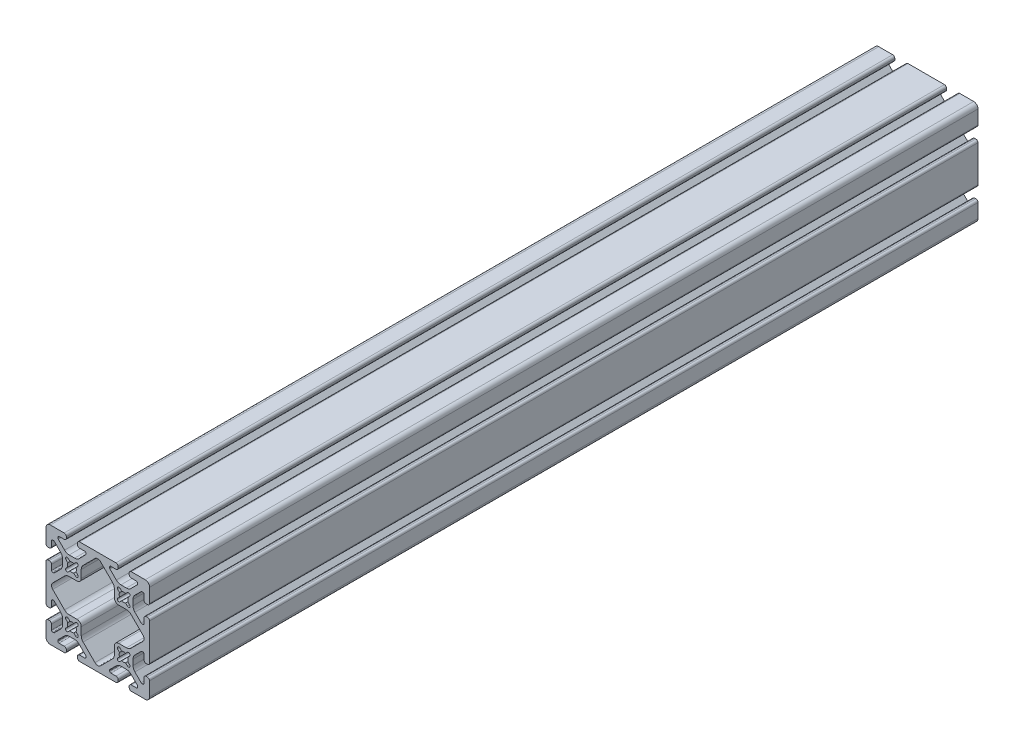
SolidWorks part; units mm, degrees
material "6063-T6"
ref_plane "Front Plane" through (0, 0, 0) normal (0, 0, 1) x (1, 0, 0)
ref_plane "Top Plane" through (0, 0, 0) normal (0, 1, 0) x (1, 0, 0)
ref_plane "Right Plane" through (0, 0, 0) normal (1, 0, 0) x (0, 0, -1)
ref_plane "Plane1" through (0, 0, -711.2) normal (0, 0, -1) x (-1, 0, 0)
sketch "Sketch1" plane through (0, 0, -711.2) normal (0, 0, -1) x (-1, 0, 0)
  line L0 (24.4372, 10.7892) -> (33.1609, 2.0655)
  line L1 (33.1609, -2.0655) -> (24.4372, -10.7892)
  line L2 (21.0785, -12.1803) -> (15.3553, -12.1803)
  line L3 (12.1803, -15.3553) -> (12.1803, -21.0785)
  line L4 (10.7892, -24.4372) -> (2.0655, -33.1609)
  line L5 (-2.0655, -33.1609) -> (-10.7892, -24.4372)
  line L6 (-12.1803, -21.0785) -> (-12.1803, -15.3553)
  line L7 (-15.3553, -12.1803) -> (-21.0785, -12.1803)
  line L8 (-24.4372, -10.7892) -> (-33.1609, -2.0655)
  line L9 (-33.1609, 2.0655) -> (-24.4372, 10.7892)
  line L10 (-21.0785, 12.1803) -> (-15.3553, 12.1803)
  line L11 (-12.1803, 15.3553) -> (-12.1803, 21.0785)
  line L12 (-10.7892, 24.4372) -> (-2.0655, 33.1609)
  line L13 (2.0655, 33.1609) -> (10.7892, 24.4372)
  line L14 (12.1803, 21.0785) -> (12.1803, 15.3553)
  line L15 (15.3553, 12.1803) -> (21.0785, 12.1803)
  line L16 (22.0679, 17.6486) -> (23.3933, 16.3231)
  line L17 (21.7769, 14.7067) -> (20.4514, 16.0321)
  line L18 (17.6486, 16.0321) -> (16.3231, 14.7067)
  line L19 (14.7067, 16.3231) -> (16.0321, 17.6486)
  line L20 (16.0321, 20.4514) -> (14.7067, 21.7769)
  line L21 (16.3231, 23.3933) -> (17.6486, 22.0679)
  line L22 (20.4514, 22.0679) -> (21.7769, 23.3933)
  line L23 (23.3933, 21.7769) -> (22.0679, 20.4514)
  line L24 (20.4514, -16.0321) -> (21.7769, -14.7067)
  line L25 (23.3933, -16.3231) -> (22.0679, -17.6486)
  line L26 (22.0679, -20.4514) -> (23.3933, -21.7769)
  line L27 (21.7769, -23.3933) -> (20.4514, -22.0679)
  line L28 (17.6486, -22.0679) -> (16.3231, -23.3933)
  line L29 (14.7067, -21.7769) -> (16.0321, -20.4514)
  line L30 (16.0321, -17.6486) -> (14.7067, -16.3231)
  line L31 (16.3231, -14.7067) -> (17.6486, -16.0321)
  line L32 (-16.0321, 17.6486) -> (-14.7067, 16.3231)
  line L33 (-16.3231, 14.7067) -> (-17.6486, 16.0321)
  line L34 (-20.4514, 16.0321) -> (-21.7769, 14.7067)
  line L35 (-23.3933, 16.3231) -> (-22.0679, 17.6486)
  line L36 (-22.0679, 20.4514) -> (-23.3933, 21.7769)
  line L37 (-21.7769, 23.3933) -> (-20.4514, 22.0679)
  line L38 (-17.6486, 22.0679) -> (-16.3231, 23.3933)
  line L39 (-14.7067, 21.7769) -> (-16.0321, 20.4514)
  line L40 (-17.6486, -16.0321) -> (-16.3231, -14.7067)
  line L41 (-14.7067, -16.3231) -> (-16.0321, -17.6486)
  line L42 (-16.0321, -20.4514) -> (-14.7067, -21.7769)
  line L43 (-16.3231, -23.3933) -> (-17.6486, -22.0679)
  line L44 (-20.4514, -22.0679) -> (-21.7769, -23.3933)
  line L45 (-23.3933, -21.7769) -> (-22.0679, -20.4514)
  line L46 (-22.0679, -17.6486) -> (-23.3933, -16.3231)
  line L47 (-21.7769, -14.7067) -> (-20.4514, -16.0321)
  line L48 (36.5252, 14.986) -> (35.6108, 14.986)
  line L49 (34.036, 13.4112) -> (34.036, 9.652)
  line L50 (33.147, 8.763) -> (32.5789, 8.763)
  line L51 (31.9503, 9.0234) -> (27.3108, 13.6628)
  line L52 (25.9197, 17.0215) -> (25.9197, 21.0785)
  line L53 (27.3108, 24.4372) -> (31.9503, 29.0766)
  line L54 (32.5789, 29.337) -> (33.147, 29.337)
  line L55 (34.036, 28.448) -> (34.036, 24.6888)
  line L56 (35.6108, 23.114) -> (36.5252, 23.114)
  line L57 (38.1, 24.6888) -> (38.1, 34.925)
  line L58 (34.925, 38.1) -> (24.6888, 38.1)
  line L59 (23.114, 36.5252) -> (23.114, 35.6108)
  line L60 (24.6888, 34.036) -> (28.448, 34.036)
  line L61 (29.337, 33.147) -> (29.337, 32.5789)
  line L62 (29.0766, 31.9503) -> (24.4372, 27.3108)
  line L63 (21.0785, 25.9197) -> (17.0215, 25.9197)
  line L64 (13.6628, 27.3108) -> (9.0234, 31.9503)
  line L65 (8.763, 32.5789) -> (8.763, 33.147)
  line L66 (9.652, 34.036) -> (13.4112, 34.036)
  line L67 (14.986, 35.6108) -> (14.986, 36.5252)
  line L68 (13.4112, 38.1) -> (-13.4112, 38.1)
  line L69 (-14.986, 36.5252) -> (-14.986, 35.6108)
  line L70 (-13.4112, 34.036) -> (-9.652, 34.036)
  line L71 (-8.763, 33.147) -> (-8.763, 32.5789)
  line L72 (-9.0234, 31.9503) -> (-13.6628, 27.3108)
  line L73 (-17.0215, 25.9197) -> (-21.0785, 25.9197)
  line L74 (-24.4372, 27.3108) -> (-29.0766, 31.9503)
  line L75 (-29.337, 32.5789) -> (-29.337, 33.147)
  line L76 (-28.448, 34.036) -> (-24.6888, 34.036)
  line L77 (-23.114, 35.6108) -> (-23.114, 36.5252)
  line L78 (-24.6888, 38.1) -> (-34.925, 38.1)
  line L79 (-38.1, 34.925) -> (-38.1, 24.6888)
  line L80 (-36.5252, 23.114) -> (-35.6108, 23.114)
  line L81 (-34.036, 24.6888) -> (-34.036, 28.448)
  line L82 (-33.147, 29.337) -> (-32.5789, 29.337)
  line L83 (-31.9503, 29.0766) -> (-27.3108, 24.4372)
  line L84 (-25.9197, 21.0785) -> (-25.9197, 17.0215)
  line L85 (-27.3108, 13.6628) -> (-31.9503, 9.0234)
  line L86 (-32.5789, 8.763) -> (-33.147, 8.763)
  line L87 (-34.036, 9.652) -> (-34.036, 13.4112)
  line L88 (-35.6108, 14.986) -> (-36.5252, 14.986)
  line L89 (-38.1, 13.4112) -> (-38.1, -13.4112)
  line L90 (-36.5252, -14.986) -> (-35.6108, -14.986)
  line L91 (-34.036, -13.4112) -> (-34.036, -9.652)
  line L92 (-33.147, -8.763) -> (-32.5789, -8.763)
  line L93 (-31.9503, -9.0234) -> (-27.3108, -13.6628)
  line L94 (-25.9197, -17.0215) -> (-25.9197, -21.0785)
  line L95 (-27.3108, -24.4372) -> (-31.9503, -29.0766)
  line L96 (-32.5789, -29.337) -> (-33.147, -29.337)
  line L97 (-34.036, -28.448) -> (-34.036, -24.6888)
  line L98 (-35.6108, -23.114) -> (-36.5252, -23.114)
  line L99 (-38.1, -24.6888) -> (-38.1, -34.925)
  line L100 (-34.925, -38.1) -> (-24.6888, -38.1)
  line L101 (-23.114, -36.5252) -> (-23.114, -35.6108)
  line L102 (-24.6888, -34.036) -> (-28.448, -34.036)
  line L103 (-29.337, -33.147) -> (-29.337, -32.5789)
  line L104 (-29.0766, -31.9503) -> (-24.4372, -27.3108)
  line L105 (-21.0785, -25.9197) -> (-17.0215, -25.9197)
  line L106 (-13.6628, -27.3108) -> (-9.0234, -31.9503)
  line L107 (-8.763, -32.5789) -> (-8.763, -33.147)
  line L108 (-9.652, -34.036) -> (-13.4112, -34.036)
  line L109 (-14.986, -35.6108) -> (-14.986, -36.5252)
  line L110 (-13.4112, -38.1) -> (13.4112, -38.1)
  line L111 (14.986, -36.5252) -> (14.986, -35.6108)
  line L112 (13.4112, -34.036) -> (9.652, -34.036)
  line L113 (8.763, -33.147) -> (8.763, -32.5789)
  line L114 (9.0234, -31.9503) -> (13.6628, -27.3108)
  line L115 (17.0215, -25.9197) -> (21.0785, -25.9197)
  line L116 (24.4372, -27.3108) -> (29.0766, -31.9503)
  line L117 (29.337, -32.5789) -> (29.337, -33.147)
  line L118 (28.448, -34.036) -> (24.6888, -34.036)
  line L119 (23.114, -35.6108) -> (23.114, -36.5252)
  line L120 (24.6888, -38.1) -> (34.925, -38.1)
  line L121 (38.1, -34.925) -> (38.1, -24.6888)
  line L122 (36.5252, -23.114) -> (35.6108, -23.114)
  line L123 (34.036, -24.6888) -> (34.036, -28.448)
  line L124 (33.147, -29.337) -> (32.5789, -29.337)
  line L125 (31.9503, -29.0766) -> (27.3108, -24.4372)
  line L126 (25.9197, -21.0785) -> (25.9197, -17.0215)
  line L127 (27.3108, -13.6628) -> (31.9503, -9.0234)
  line L128 (32.5789, -8.763) -> (33.147, -8.763)
  line L129 (34.036, -9.652) -> (34.036, -13.4112)
  line L130 (35.6108, -14.986) -> (36.5252, -14.986)
  line L131 (38.1, -13.4112) -> (38.1, 13.4112)
  arc A0 (33.1609, 2.0655) -> (33.1609, -2.0655) centre (31.0954, 0) cw
  arc A1 (24.4372, -10.7892) -> (21.0785, -12.1803) centre (21.0785, -7.4305) cw
  arc A2 (15.3553, -12.1803) -> (12.1803, -15.3553) centre (15.3553, -15.3553) ccw
  arc A3 (12.1803, -21.0785) -> (10.7892, -24.4372) centre (7.4305, -21.0785) cw
  arc A4 (2.0655, -33.1609) -> (-2.0655, -33.1609) centre (0, -31.0954) cw
  arc A5 (-10.7892, -24.4372) -> (-12.1803, -21.0785) centre (-7.4305, -21.0785) cw
  arc A6 (-12.1803, -15.3553) -> (-15.3553, -12.1803) centre (-15.3553, -15.3553) ccw
  arc A7 (-21.0785, -12.1803) -> (-24.4372, -10.7892) centre (-21.0785, -7.4305) cw
  arc A8 (-33.1609, -2.0655) -> (-33.1609, 2.0655) centre (-31.0954, 0) cw
  arc A9 (-24.4372, 10.7892) -> (-21.0785, 12.1803) centre (-21.0785, 7.4305) cw
  arc A10 (-15.3553, 12.1803) -> (-12.1803, 15.3553) centre (-15.3553, 15.3553) ccw
  arc A11 (-12.1803, 21.0785) -> (-10.7892, 24.4372) centre (-7.4305, 21.0785) cw
  arc A12 (-2.0655, 33.1609) -> (2.0655, 33.1609) centre (0, 31.0954) cw
  arc A13 (10.7892, 24.4372) -> (12.1803, 21.0785) centre (7.4305, 21.0785) cw
  arc A14 (12.1803, 15.3553) -> (15.3553, 12.1803) centre (15.3553, 15.3553) ccw
  arc A15 (21.0785, 12.1803) -> (24.4372, 10.7892) centre (21.0785, 7.4305) cw
  arc A16 (23.3933, 16.3231) -> (21.7769, 14.7067) centre (22.5851, 15.5149) cw
  arc A17 (20.4514, 16.0321) -> (17.6486, 16.0321) centre (19.05, 19.05) cw
  arc A18 (16.3231, 14.7067) -> (14.7067, 16.3231) centre (15.5149, 15.5149) cw
  arc A19 (16.0321, 17.6486) -> (16.0321, 20.4514) centre (19.05, 19.05) cw
  arc A20 (14.7067, 21.7769) -> (16.3231, 23.3933) centre (15.5149, 22.5851) cw
  arc A21 (17.6486, 22.0679) -> (20.4514, 22.0679) centre (19.05, 19.05) cw
  arc A22 (21.7769, 23.3933) -> (23.3933, 21.7769) centre (22.5851, 22.5851) cw
  arc A23 (22.0679, 20.4514) -> (22.0679, 17.6486) centre (19.05, 19.05) cw
  arc A24 (21.7769, -14.7067) -> (23.3933, -16.3231) centre (22.5851, -15.5149) cw
  arc A25 (22.0679, -17.6486) -> (22.0679, -20.4514) centre (19.05, -19.05) cw
  arc A26 (23.3933, -21.7769) -> (21.7769, -23.3933) centre (22.5851, -22.5851) cw
  arc A27 (20.4514, -22.0679) -> (17.6486, -22.0679) centre (19.05, -19.05) cw
  arc A28 (16.3231, -23.3933) -> (14.7067, -21.7769) centre (15.5149, -22.5851) cw
  arc A29 (16.0321, -20.4514) -> (16.0321, -17.6486) centre (19.05, -19.05) cw
  arc A30 (14.7067, -16.3231) -> (16.3231, -14.7067) centre (15.5149, -15.5149) cw
  arc A31 (17.6486, -16.0321) -> (20.4514, -16.0321) centre (19.05, -19.05) cw
  arc A32 (-14.7067, 16.3231) -> (-16.3231, 14.7067) centre (-15.5149, 15.5149) cw
  arc A33 (-17.6486, 16.0321) -> (-20.4514, 16.0321) centre (-19.05, 19.05) cw
  arc A34 (-21.7769, 14.7067) -> (-23.3933, 16.3231) centre (-22.5851, 15.5149) cw
  arc A35 (-22.0679, 17.6486) -> (-22.0679, 20.4514) centre (-19.05, 19.05) cw
  arc A36 (-23.3933, 21.7769) -> (-21.7769, 23.3933) centre (-22.5851, 22.5851) cw
  arc A37 (-20.4514, 22.0679) -> (-17.6486, 22.0679) centre (-19.05, 19.05) cw
  arc A38 (-16.3231, 23.3933) -> (-14.7067, 21.7769) centre (-15.5149, 22.5851) cw
  arc A39 (-16.0321, 20.4514) -> (-16.0321, 17.6486) centre (-19.05, 19.05) cw
  arc A40 (-16.3231, -14.7067) -> (-14.7067, -16.3231) centre (-15.5149, -15.5149) cw
  arc A41 (-16.0321, -17.6486) -> (-16.0321, -20.4514) centre (-19.05, -19.05) cw
  arc A42 (-14.7067, -21.7769) -> (-16.3231, -23.3933) centre (-15.5149, -22.5851) cw
  arc A43 (-17.6486, -22.0679) -> (-20.4514, -22.0679) centre (-19.05, -19.05) cw
  arc A44 (-21.7769, -23.3933) -> (-23.3933, -21.7769) centre (-22.5851, -22.5851) cw
  arc A45 (-22.0679, -20.4514) -> (-22.0679, -17.6486) centre (-19.05, -19.05) cw
  arc A46 (-23.3933, -16.3231) -> (-21.7769, -14.7067) centre (-22.5851, -15.5149) cw
  arc A47 (-20.4514, -16.0321) -> (-17.6486, -16.0321) centre (-19.05, -19.05) cw
  arc A48 (38.1, 13.4112) -> (36.5252, 14.986) centre (36.5252, 13.4112) ccw
  arc A49 (35.6108, 14.986) -> (34.036, 13.4112) centre (35.6108, 13.4112) ccw
  arc A50 (34.036, 9.652) -> (33.147, 8.763) centre (33.147, 9.652) cw
  arc A51 (32.5789, 8.763) -> (31.9503, 9.0234) centre (32.5789, 9.652) cw
  arc A52 (27.3108, 13.6628) -> (25.9197, 17.0215) centre (30.6695, 17.0215) cw
  arc A53 (25.9197, 21.0785) -> (27.3108, 24.4372) centre (30.6695, 21.0785) cw
  arc A54 (31.9503, 29.0766) -> (32.5789, 29.337) centre (32.5789, 28.448) cw
  arc A55 (33.147, 29.337) -> (34.036, 28.448) centre (33.147, 28.448) cw
  arc A56 (34.036, 24.6888) -> (35.6108, 23.114) centre (35.6108, 24.6888) ccw
  arc A57 (36.5252, 23.114) -> (38.1, 24.6888) centre (36.5252, 24.6888) ccw
  arc A58 (38.1, 34.925) -> (34.925, 38.1) centre (34.925, 34.925) ccw
  arc A59 (24.6888, 38.1) -> (23.114, 36.5252) centre (24.6888, 36.5252) ccw
  arc A60 (23.114, 35.6108) -> (24.6888, 34.036) centre (24.6888, 35.6108) ccw
  arc A61 (28.448, 34.036) -> (29.337, 33.147) centre (28.448, 33.147) cw
  arc A62 (29.337, 32.5789) -> (29.0766, 31.9503) centre (28.448, 32.5789) cw
  arc A63 (24.4372, 27.3108) -> (21.0785, 25.9197) centre (21.0785, 30.6695) cw
  arc A64 (17.0215, 25.9197) -> (13.6628, 27.3108) centre (17.0215, 30.6695) cw
  arc A65 (9.0234, 31.9503) -> (8.763, 32.5789) centre (9.652, 32.5789) cw
  arc A66 (8.763, 33.147) -> (9.652, 34.036) centre (9.652, 33.147) cw
  arc A67 (13.4112, 34.036) -> (14.986, 35.6108) centre (13.4112, 35.6108) ccw
  arc A68 (14.986, 36.5252) -> (13.4112, 38.1) centre (13.4112, 36.5252) ccw
  arc A69 (-13.4112, 38.1) -> (-14.986, 36.5252) centre (-13.4112, 36.5252) ccw
  arc A70 (-14.986, 35.6108) -> (-13.4112, 34.036) centre (-13.4112, 35.6108) ccw
  arc A71 (-9.652, 34.036) -> (-8.763, 33.147) centre (-9.652, 33.147) cw
  arc A72 (-8.763, 32.5789) -> (-9.0234, 31.9503) centre (-9.652, 32.5789) cw
  arc A73 (-13.6628, 27.3108) -> (-17.0215, 25.9197) centre (-17.0215, 30.6695) cw
  arc A74 (-21.0785, 25.9197) -> (-24.4372, 27.3108) centre (-21.0785, 30.6695) cw
  arc A75 (-29.0766, 31.9503) -> (-29.337, 32.5789) centre (-28.448, 32.5789) cw
  arc A76 (-29.337, 33.147) -> (-28.448, 34.036) centre (-28.448, 33.147) cw
  arc A77 (-24.6888, 34.036) -> (-23.114, 35.6108) centre (-24.6888, 35.6108) ccw
  arc A78 (-23.114, 36.5252) -> (-24.6888, 38.1) centre (-24.6888, 36.5252) ccw
  arc A79 (-34.925, 38.1) -> (-38.1, 34.925) centre (-34.925, 34.925) ccw
  arc A80 (-38.1, 24.6888) -> (-36.5252, 23.114) centre (-36.5252, 24.6888) ccw
  arc A81 (-35.6108, 23.114) -> (-34.036, 24.6888) centre (-35.6108, 24.6888) ccw
  arc A82 (-34.036, 28.448) -> (-33.147, 29.337) centre (-33.147, 28.448) cw
  arc A83 (-32.5789, 29.337) -> (-31.9503, 29.0766) centre (-32.5789, 28.448) cw
  arc A84 (-27.3108, 24.4372) -> (-25.9197, 21.0785) centre (-30.6695, 21.0785) cw
  arc A85 (-25.9197, 17.0215) -> (-27.3108, 13.6628) centre (-30.6695, 17.0215) cw
  arc A86 (-31.9503, 9.0234) -> (-32.5789, 8.763) centre (-32.5789, 9.652) cw
  arc A87 (-33.147, 8.763) -> (-34.036, 9.652) centre (-33.147, 9.652) cw
  arc A88 (-34.036, 13.4112) -> (-35.6108, 14.986) centre (-35.6108, 13.4112) ccw
  arc A89 (-36.5252, 14.986) -> (-38.1, 13.4112) centre (-36.5252, 13.4112) ccw
  arc A90 (-38.1, -13.4112) -> (-36.5252, -14.986) centre (-36.5252, -13.4112) ccw
  arc A91 (-35.6108, -14.986) -> (-34.036, -13.4112) centre (-35.6108, -13.4112) ccw
  arc A92 (-34.036, -9.652) -> (-33.147, -8.763) centre (-33.147, -9.652) cw
  arc A93 (-32.5789, -8.763) -> (-31.9503, -9.0234) centre (-32.5789, -9.652) cw
  arc A94 (-27.3108, -13.6628) -> (-25.9197, -17.0215) centre (-30.6695, -17.0215) cw
  arc A95 (-25.9197, -21.0785) -> (-27.3108, -24.4372) centre (-30.6695, -21.0785) cw
  arc A96 (-31.9503, -29.0766) -> (-32.5789, -29.337) centre (-32.5789, -28.448) cw
  arc A97 (-33.147, -29.337) -> (-34.036, -28.448) centre (-33.147, -28.448) cw
  arc A98 (-34.036, -24.6888) -> (-35.6108, -23.114) centre (-35.6108, -24.6888) ccw
  arc A99 (-36.5252, -23.114) -> (-38.1, -24.6888) centre (-36.5252, -24.6888) ccw
  arc A100 (-38.1, -34.925) -> (-34.925, -38.1) centre (-34.925, -34.925) ccw
  arc A101 (-24.6888, -38.1) -> (-23.114, -36.5252) centre (-24.6888, -36.5252) ccw
  arc A102 (-23.114, -35.6108) -> (-24.6888, -34.036) centre (-24.6888, -35.6108) ccw
  arc A103 (-28.448, -34.036) -> (-29.337, -33.147) centre (-28.448, -33.147) cw
  arc A104 (-29.337, -32.5789) -> (-29.0766, -31.9503) centre (-28.448, -32.5789) cw
  arc A105 (-24.4372, -27.3108) -> (-21.0785, -25.9197) centre (-21.0785, -30.6695) cw
  arc A106 (-17.0215, -25.9197) -> (-13.6628, -27.3108) centre (-17.0215, -30.6695) cw
  arc A107 (-9.0234, -31.9503) -> (-8.763, -32.5789) centre (-9.652, -32.5789) cw
  arc A108 (-8.763, -33.147) -> (-9.652, -34.036) centre (-9.652, -33.147) cw
  arc A109 (-13.4112, -34.036) -> (-14.986, -35.6108) centre (-13.4112, -35.6108) ccw
  arc A110 (-14.986, -36.5252) -> (-13.4112, -38.1) centre (-13.4112, -36.5252) ccw
  arc A111 (13.4112, -38.1) -> (14.986, -36.5252) centre (13.4112, -36.5252) ccw
  arc A112 (14.986, -35.6108) -> (13.4112, -34.036) centre (13.4112, -35.6108) ccw
  arc A113 (9.652, -34.036) -> (8.763, -33.147) centre (9.652, -33.147) cw
  arc A114 (8.763, -32.5789) -> (9.0234, -31.9503) centre (9.652, -32.5789) cw
  arc A115 (13.6628, -27.3108) -> (17.0215, -25.9197) centre (17.0215, -30.6695) cw
  arc A116 (21.0785, -25.9197) -> (24.4372, -27.3108) centre (21.0785, -30.6695) cw
  arc A117 (29.0766, -31.9503) -> (29.337, -32.5789) centre (28.448, -32.5789) cw
  arc A118 (29.337, -33.147) -> (28.448, -34.036) centre (28.448, -33.147) cw
  arc A119 (24.6888, -34.036) -> (23.114, -35.6108) centre (24.6888, -35.6108) ccw
  arc A120 (23.114, -36.5252) -> (24.6888, -38.1) centre (24.6888, -36.5252) ccw
  arc A121 (34.925, -38.1) -> (38.1, -34.925) centre (34.925, -34.925) ccw
  arc A122 (38.1, -24.6888) -> (36.5252, -23.114) centre (36.5252, -24.6888) ccw
  arc A123 (35.6108, -23.114) -> (34.036, -24.6888) centre (35.6108, -24.6888) ccw
  arc A124 (34.036, -28.448) -> (33.147, -29.337) centre (33.147, -28.448) cw
  arc A125 (32.5789, -29.337) -> (31.9503, -29.0766) centre (32.5789, -28.448) cw
  arc A126 (27.3108, -24.4372) -> (25.9197, -21.0785) centre (30.6695, -21.0785) cw
  arc A127 (25.9197, -17.0215) -> (27.3108, -13.6628) centre (30.6695, -17.0215) cw
  arc A128 (31.9503, -9.0234) -> (32.5789, -8.763) centre (32.5789, -9.652) cw
  arc A129 (33.147, -8.763) -> (34.036, -9.652) centre (33.147, -9.652) cw
  arc A130 (34.036, -13.4112) -> (35.6108, -14.986) centre (35.6108, -13.4112) ccw
  arc A131 (36.5252, -14.986) -> (38.1, -13.4112) centre (36.5252, -13.4112) ccw
extrude "Boss-Extrude1" add sketch "Sketch1" against normal blind 609.6
